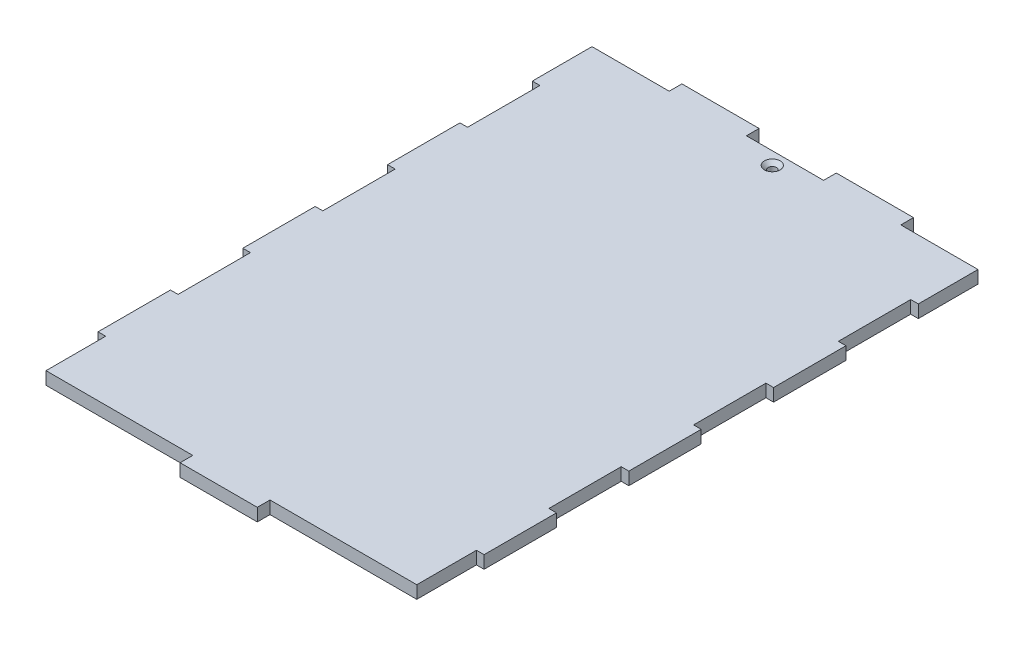
SolidWorks part; units mm, degrees
ref_plane "Front Plane" through (0, 0, 0) normal (0, 0, 1) x (1, 0, 0)
ref_plane "Top Plane" through (0, 0, 0) normal (0, 1, 0) x (1, 0, 0)
ref_plane "Right Plane" through (0, 0, 0) normal (1, 0, 0) x (0, 0, -1)
sketch "Sketch1" plane through (0, 0, 0) normal (0, 1, 0) x (1, 0, 0)
  line L0 (0, -114) -> (-15.2, -114)
  line L1 (-76, -114) -> (76, -114) construction
  line L2 (-76, -114) -> (-76, 114) construction
  line L3 (-76, 114) -> (76, 114) construction
  line L4 (76, -114) -> (76, 114) construction
  line L5 (0, 109) -> (0, -114)
  line L6 (-76, 0) -> (76, 0) construction
  line L7 (-15.2, -114) -> (-15.2, -109)
  line L8 (-15.2, -109) -> (-73, -109)
  line L25 (-73, -109) -> (-73, -85.5)
  line L26 (-73, -85.5) -> (-76, -85.5)
  line L27 (-76, -57) -> (-73, -57)
  line L28 (-73, -57) -> (-73, -28.5)
  line L29 (-73, -28.5) -> (-76, -28.5)
  line L30 (-76, -28.5) -> (-76, 0)
  line L31 (-76, -85.5) -> (-76, -57)
  line L32 (-76, 0) -> (-73, 0)
  line L33 (-73, 0) -> (-73, 28.5)
  line L34 (-73, 28.5) -> (-76, 28.5)
  line L35 (-76, 28.5) -> (-76, 57)
  line L36 (-76, 57) -> (-73, 57)
  line L37 (-73, 57) -> (-73, 85.5)
  line L38 (-73, 85.5) -> (-76, 85.5)
  line L42 (-76, 109) -> (-76, 85.5)
  line L43 (0, 109) -> (-15.2, 109)
  line L44 (-15.2, 109) -> (-15.2, 114)
  line L45 (-15.2, 114) -> (-45.6, 114)
  line L46 (-45.6, 114) -> (-45.6, 109)
  line L47 (-45.6, 109) -> (-76, 109)
  point P128 (0, 0)
  dimension "D1" = 152
  dimension "D2" = 228
  dimension "D5" = 5
  dimension "D3" = 60.8
  dimension "D4" = 28.5
  dimension "D6" = 3
  dimension "D7" = 28.5
  dimension "D8" = 28.5
  dimension "D9" = 28.5
  dimension "D10" = 28.5
  dimension "D11" = 28.5
  dimension "D12" = 28.5
  dimension "D13" = 5
  dimension "D14" = 30.4
extrude "Boss-Extrude1" add sketch "Sketch1" along normal blind 5
mirror "Mirror1" about plane through (0, 5, 0) normal (1, 0, 0) of "Boss-Extrude1"
sketch "Sketch2" plane through (0, 5, 0) normal (0, 1, 0) x (1, 0, 0)
  line L0 (15.2, 109) -> (-15.2, 109) construction
  circle A0 centre (0, 104) radius 1.6
  dimension "D2" = 3.2
  dimension "D1" = 5
extrude "Cut-Extrude1" cut sketch "Sketch2" against normal through all
chamfer "Chamfer1" distance 1.5 1 edges at (0, 5, -102.4)
equation "\"3mm akryyli\"= 3mm"
equation "\"5mm akryyli\"= 5mm"
equation "\"D5@Sketch1\"=\"5mm akryyli\""
equation "\"D6@Sketch1\"=\"3mm akryyli\""
equation "\"D13@Sketch1\"=\"5mm akryyli\""
